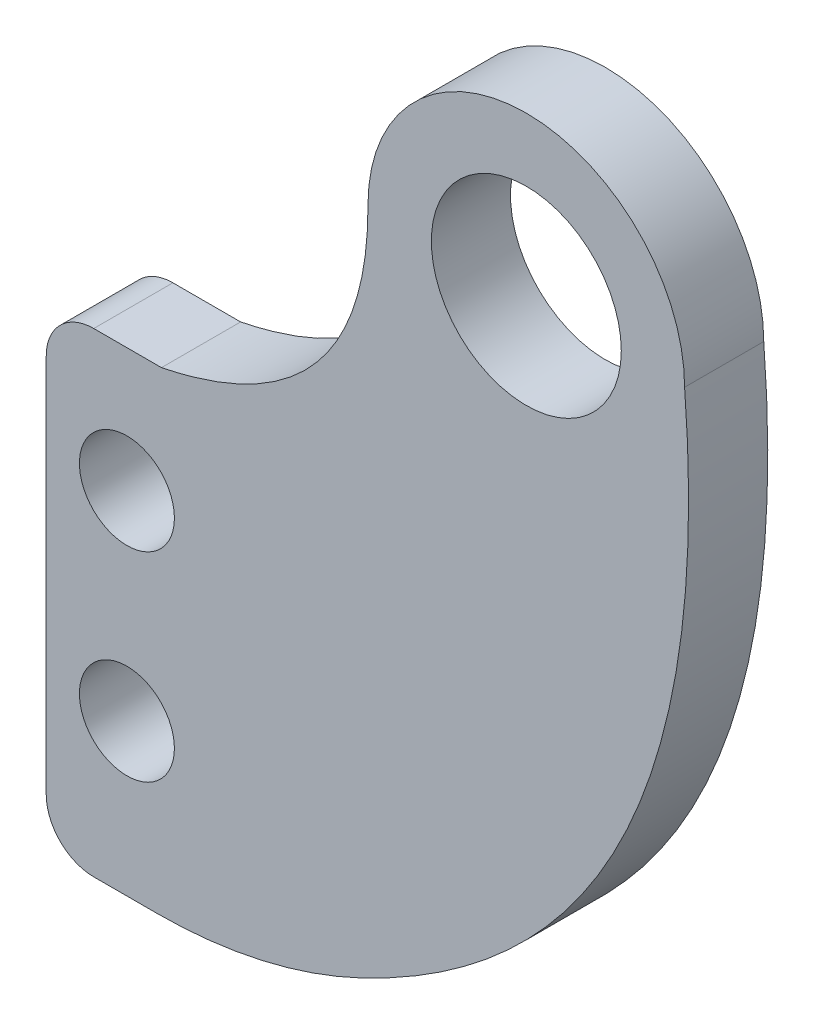
SolidWorks part; units mm, degrees
ref_plane "Front Plane" through (0, 0, 0) normal (0, 0, 1) x (1, 0, 0)
ref_plane "Top Plane" through (0, 0, 0) normal (0, 1, 0) x (1, 0, 0)
ref_plane "Right Plane" through (0, 0, 0) normal (1, 0, 0) x (0, 0, -1)
sketch "Sketch1" plane through (0, 0, 0) normal (0, 0, 1) x (1, 0, 0)
  line L0 (685.3525, 849.163) -> (685.3525, 879.163)
  line L1 (685.3525, 879.163) -> (692.6319, 879.163)
  line L2 (685.3525, 849.163) -> (697.4485, 849.163)
  circle A0 centre (690.4485, 858.7392) radius 3
  circle A1 centre (690.4485, 871.3392) radius 3
  circle A2 centre (715.6785, 894.6117) radius 6
  arc A3 (725.6785, 894.6117) -> (705.6786, 894.5731) centre (715.6785, 894.6117) ccw
  spline S0 degree 2 poles (705.6785, 894.6117) (705.713, 881.815) (692.6319, 879.163) knots 0 0 0 1 1 1
  spline S1 degree 2 poles (697.4485, 849.163) (728.6162, 858.089) (725.6785, 894.6117) knots 0 0 0 1 1 1
extrude "Boss-Extrude1" add sketch "Sketch1" along normal blind 5 contours L2 S1 A3 S0 L1 L0 A0 A1 A2
fillet "Fillet1" radius 30 3 edges at (697.4485, 849.163, 2.5)
fillet "Fillet3" radius 3 1 edges at (685.3525, 879.163, 2.5)
fillet "Fillet4" radius 3 1 edges at (685.3525, 849.163, 2.5)
